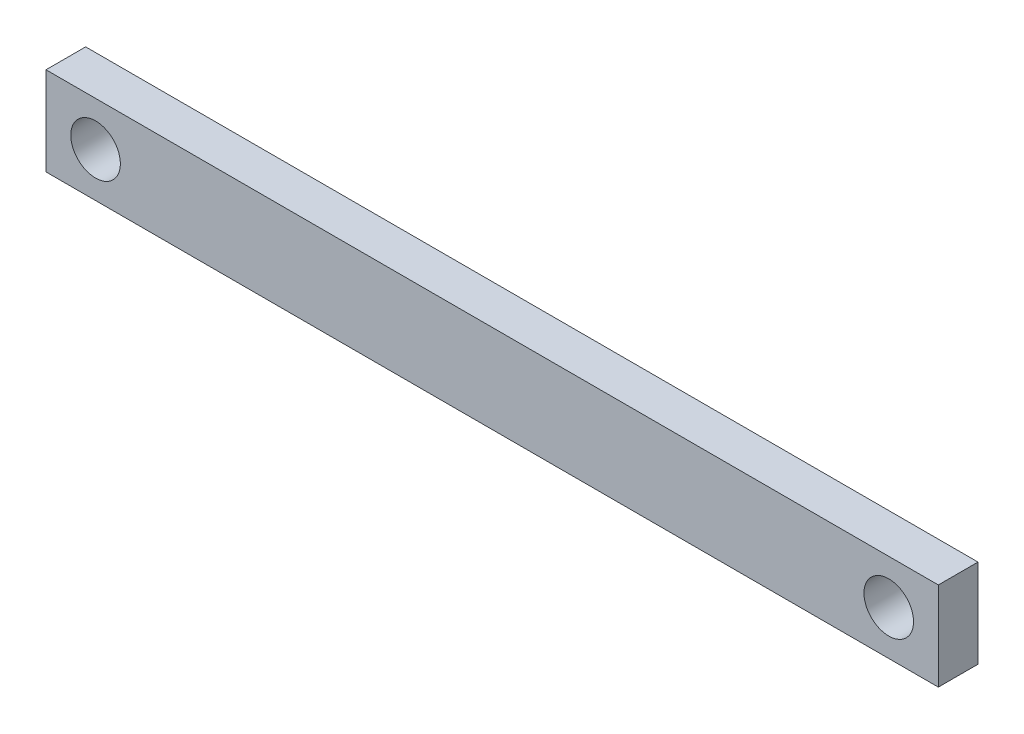
SolidWorks part; units mm, degrees
ref_plane "Plan de face" through (0, 0, 0) normal (0, 0, 1) x (1, 0, 0)
ref_plane "Plan de dessus" through (0, 0, 0) normal (0, 1, 0) x (1, 0, 0)
ref_plane "Plan de droite" through (0, 0, 0) normal (1, 0, 0) x (0, 0, -1)
sketch "Esquisse1" plane through (0, 0, 0) normal (0, 0, 1) x (1, 0, 0)
  line L0 (0, 0) -> (0, 20.2834) construction
  line L1 (-45, -4.4631) -> (45, -4.4631)
  line L2 (-45, -4.4631) -> (-45, 4.4631)
  line L3 (-45, 4.4631) -> (45, 4.4631)
  line L4 (45, -4.4631) -> (45, 4.4631)
  line L5 (-45, -4.4631) -> (45, 4.4631) construction
  line L6 (-45, 4.4631) -> (45, -4.4631) construction
  line L7 (45, 0) -> (-45, 0) construction
  circle A0 centre (-40, 0) radius 2.5
  circle A1 centre (40, 0) radius 2.5
  point P0 (0, 0)
  dimension "D1" = 5
  dimension "D2" = 40
  dimension "D3" = 90
extrude "BASE" add sketch "Esquisse1" along normal blind 4
